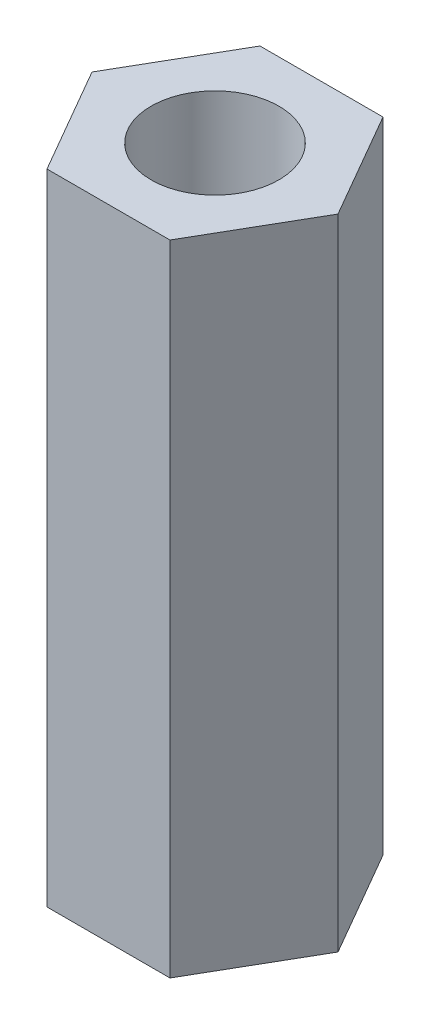
SolidWorks part; units mm, degrees
material "Latón"
ref_plane "Alzado" through (0, 0, 0) normal (0, 0, 1) x (1, 0, 0)
ref_plane "Planta" through (0, 0, 0) normal (0, 1, 0) x (1, 0, 0)
ref_plane "Vista lateral" through (0, 0, 0) normal (1, 0, 0) x (0, 0, -1)
sketch "Croquis1" plane through (0, 0, 0) normal (0, 1, 0) x (1, 0, 0)
  line L1 (1.4434, -2.5) -> (2.8868, 0)
  line L2 (2.8868, 0) -> (1.4434, 2.5)
  line L3 (1.4434, 2.5) -> (-1.4434, 2.5)
  line L4 (-1.4434, 2.5) -> (-2.8868, 0)
  line L5 (-2.8868, 0) -> (-1.4434, -2.5)
  line L6 (-1.4434, -2.5) -> (1.4434, -2.5)
  circle A0 centre (0, 0) radius 2.5 construction
  circle A1 centre (0, 0) radius 1.5
  dimension "D2" = 3
  dimension "D1" = 5
extrude "Saliente-Extruir1" add sketch "Croquis1" along normal mid plane 15
